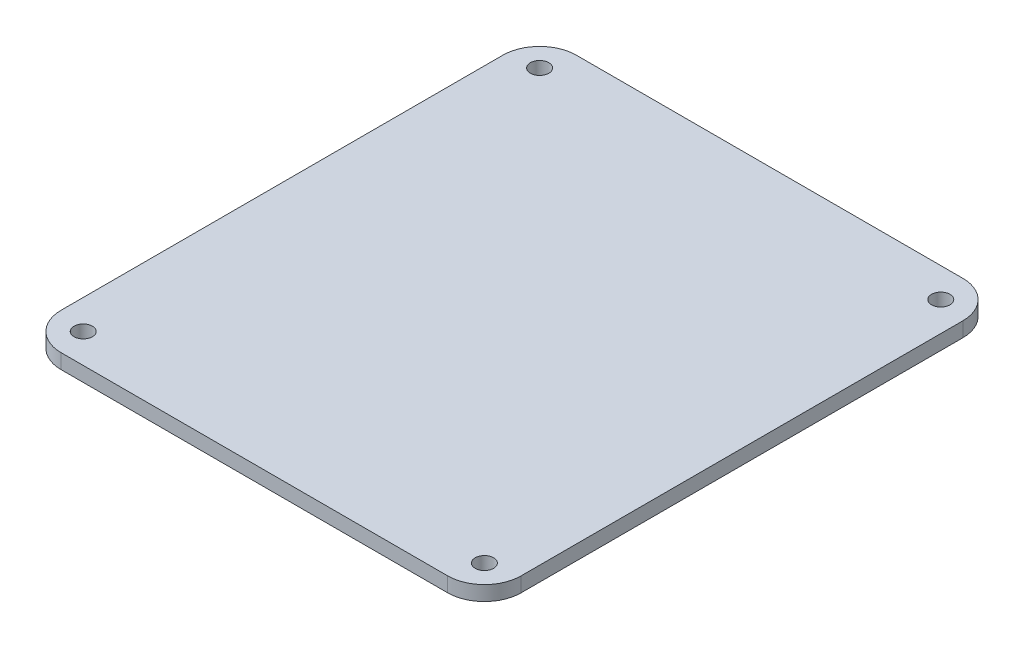
SolidWorks part; units mm, degrees
material "1060 Alloy"
ref_plane "Front Plane" through (0, 0, 0) normal (0, 0, 1) x (1, 0, 0)
ref_plane "Top Plane" through (0, 0, 0) normal (0, 1, 0) x (1, 0, 0)
ref_plane "Right Plane" through (0, 0, 0) normal (1, 0, 0) x (0, 0, -1)
sketch "Sketch1" plane through (0, 0, 0) normal (0, 1, 0) x (1, 0, 0)
  line L1 (-62.5, -70) -> (62.5, -70)
  line L2 (-62.5, -70) -> (-62.5, 70)
  line L3 (-62.5, 70) -> (62.5, 70)
  line L4 (62.5, -70) -> (62.5, 70)
  line L5 (-62.5, -70) -> (62.5, 70) construction
  line L6 (-62.5, 70) -> (62.5, -70) construction
  point P0 (0, 0)
  dimension "D1" = 140
  dimension "D2" = 125
extrude "Boss-Extrude1" add sketch "Sketch1" along normal blind 4
sketch "Sketch2" plane through (0, 4, 0) normal (0, 1, 0) x (1, 0, 0)
  line L0 (62.5, -70) -> (62.5, 70) construction
  line L1 (62.5, 50) -> (50.5, 50)
  line L2 (62.5, 50) -> (62.5, 27)
  line L3 (62.5, 27) -> (50.5, 27)
  line L4 (50.5, 50) -> (50.5, 27)
  line L5 (-62.5, 70) -> (-62.5, -70) construction
  line L6 (-62.5, 50) -> (-50.5, 50)
  line L7 (-62.5, 50) -> (-62.5, 27)
  line L8 (-62.5, 27) -> (-50.5, 27)
  line L9 (-50.5, 50) -> (-50.5, 27)
  line L10 (-50.5, 0) -> (0, 0) construction
  line L19 (62.5, -27) -> (50.5, -27)
  line L20 (62.5, -27) -> (62.5, -50)
  line L21 (62.5, -50) -> (50.5, -50)
  line L22 (50.5, -27) -> (50.5, -50)
  line L23 (-62.5, -27) -> (-50.5, -27)
  line L24 (-62.5, -27) -> (-62.5, -50)
  line L25 (-62.5, -50) -> (-50.5, -50)
  line L26 (-50.5, -27) -> (-50.5, -50)
  line L27 (0, 0) -> (50.5, 0) construction
  line L28 (-56.5, 52.65) -> (-56.5, 50) construction
  line L29 (-62.5, -70) -> (62.5, -70) construction
  line L30 (62.5, 70) -> (-62.5, 70) construction
  line L31 (-56.5, 24.35) -> (-56.5, 27) construction
  line L32 (-62.5, 17) -> (-50.5, 17)
  line L33 (-62.5, 17) -> (-62.5, -17)
  line L34 (-62.5, -17) -> (-50.5, -17)
  line L35 (-50.5, 17) -> (-50.5, -17)
  line L36 (62.5, 17) -> (50.5, 17)
  line L37 (62.5, 17) -> (62.5, -17)
  line L38 (62.5, -17) -> (50.5, -17)
  line L39 (50.5, 17) -> (50.5, -17)
  line L40 (-56.5, -24.35) -> (-56.5, -27) construction
  line L41 (-56.5, -50) -> (-56.5, -52.65) construction
  line L42 (56.5, 52.65) -> (56.5, 50) construction
  line L43 (56.5, 24.35) -> (56.5, 27) construction
  line L44 (56.5, -24.35) -> (56.5, -27) construction
  line L45 (56.5, -50) -> (56.5, -52.65) construction
  circle A2 centre (-56.5, 52.65) radius 1.1
  circle A3 centre (-56.5, 24.35) radius 1.1
  circle A4 centre (-56.5, -24.35) radius 1.1
  circle A5 centre (-56.5, -52.65) radius 1.1
  circle A6 centre (56.5, 52.65) radius 1.1
  circle A7 centre (56.5, 24.35) radius 1.1
  circle A8 centre (56.5, -24.35) radius 1.1
  circle A9 centre (56.5, -52.65) radius 1.1
  circle A10 centre (-54.5, 62) radius 2.5
  circle A11 centre (54.5, 62) radius 2.5
  circle A12 centre (54.5, -62) radius 2.5
  circle A13 centre (-54.5, -62) radius 2.5
  dimension "D6" = 2.2
  dimension "D15" = 5
  dimension "D1" = 23
  dimension "D2" = 12
  dimension "D3" = 20
  dimension "D4" = 20
  dimension "D5" = 10
  dimension "D7" = 2.65
  dimension "D8" = 2.65
  dimension "D9" = 2.65
  dimension "D10" = 2.65
  dimension "D11" = 2.65
  dimension "D12" = 2.65
  dimension "D13" = 2.65
  dimension "D14" = 2.65
  dimension "D16" = 8
  dimension "D17" = 8
  dimension "D18" = 8
  dimension "D19" = 8
  dimension "D20" = 8
  dimension "D21" = 8
  dimension "D22" = 8
  dimension "D23" = 8
extrude "Cut-Extrude1" cut sketch "Sketch2" against normal through all contours A10 | A11 | A13 | A12
fillet "Fillet2" radius 10 4 edges at (62.5, 2, 70) (-62.5, 2, 70) (-62.5, 2, -70) (62.5, 2, -70)
